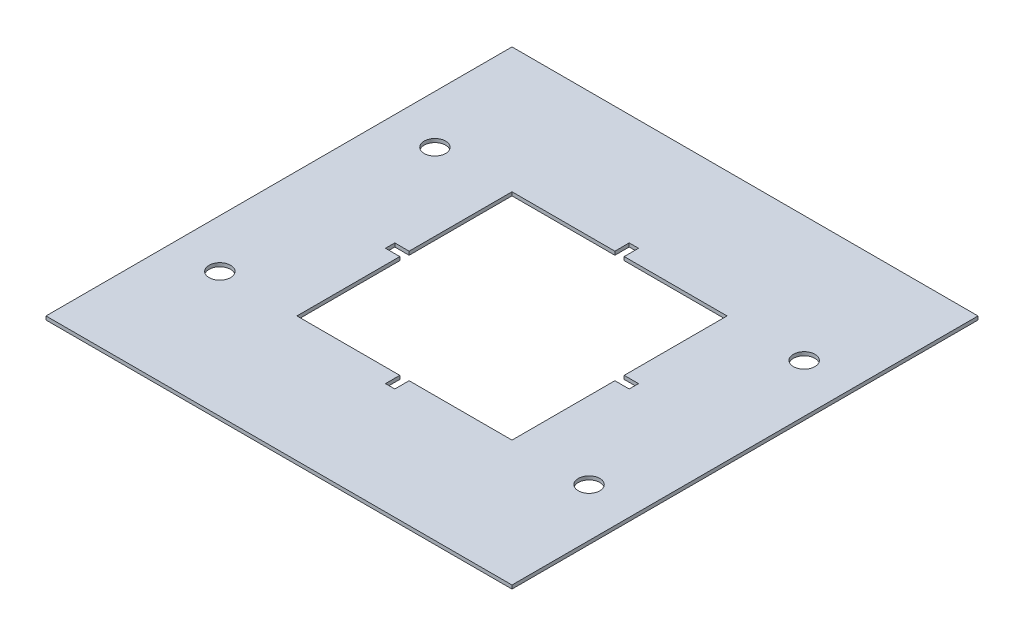
SolidWorks part; units mm, degrees
ref_plane "Alzado" through (0, 0, 0) normal (0, 0, 1) x (1, 0, 0)
ref_plane "Planta" through (0, 0, 0) normal (0, 1, 0) x (1, 0, 0)
ref_plane "Vista lateral" through (0, 0, 0) normal (1, 0, 0) x (0, 0, -1)
sketch "Croquis1" plane through (0, 0, 0) normal (0, 1, 0) x (1, 0, 0)
  line L0 (0, 0) -> (55, 55) construction
  line L1 (0, 0) -> (55, 0)
  line L2 (0, 0) -> (0, 55)
  line L3 (0, 55) -> (55, 55)
  line L4 (55, 0) -> (55, 55)
  line L5 (1.75, 0) -> (1.75, 55) construction
  line L6 (12.5, 12.5) -> (26.85, 12.5)
  line L7 (12.5, 12.5) -> (12.5, 26.85)
  line L8 (12.5, 42.5) -> (26.85, 42.5)
  line L9 (42.5, 12.5) -> (42.5, 26.85)
  line L10 (12.5, 12.5) -> (42.5, 42.5) construction
  line L11 (12.5, 42.5) -> (42.5, 12.5) construction
  line L12 (27.5, 0) -> (27.5, 55) construction
  line L13 (3.5, 0) -> (3.5, 55) construction
  line L14 (3.5, 27.5) -> (0, 27.5) construction
  line L15 (3.25, 42.5) -> (3.25, 27.5) construction
  line L16 (3.25, 27.5) -> (3.25, 12.5) construction
  line L17 (0, 27.5) -> (55, 27.5) construction
  line L18 (26.85, 44.5) -> (28.15, 44.5)
  line L19 (26.85, 44.5) -> (26.85, 42.5)
  line L21 (28.15, 44.5) -> (28.15, 42.5)
  line L22 (26.85, 44.5) -> (28.15, 42.5) construction
  line L23 (26.85, 42.5) -> (28.15, 44.5) construction
  line L25 (44.5, 28.15) -> (42.5, 28.15)
  line L26 (44.5, 28.15) -> (44.5, 26.85)
  line L27 (44.5, 26.85) -> (42.5, 26.85)
  line L29 (44.5, 28.15) -> (42.5, 26.85) construction
  line L30 (44.5, 26.85) -> (42.5, 28.15) construction
  line L31 (28.15, 10.5) -> (28.15, 12.5)
  line L32 (26.85, 10.5) -> (26.85, 12.5)
  line L33 (26.85, 10.5) -> (28.15, 10.5)
  line L34 (10.5, 26.85) -> (12.5, 26.85)
  line L36 (10.5, 28.15) -> (12.5, 28.15)
  line L37 (10.5, 28.15) -> (10.5, 26.85)
  line L38 (42.5, 28.15) -> (42.5, 42.5)
  line L39 (28.15, 12.5) -> (42.5, 12.5)
  line L40 (12.5, 28.15) -> (12.5, 42.5)
  line L41 (28.15, 42.5) -> (42.5, 42.5)
  circle A0 centre (1.75, 42.5) radius 1.5
  circle A1 centre (1.75, 12.5) radius 1.5
  circle A2 centre (53.25, 42.5) radius 1.5
  circle A3 centre (53.25, 12.5) radius 1.5
  point P4 (27.5, 27.5)
  point P18 (1.75, 27.5)
  point P25 (27.5, 43.5)
  point P35 (43.5, 27.5)
  dimension "D4" = 3
  dimension "D1" = 55
  dimension "D2" = 30
  dimension "D3" = 24
  dimension "D5" = 15
  dimension "D6" = 1.3
  dimension "D7" = 2
extrude "Saliente-Extruir1" add sketch "Croquis1" along normal blind 0.5
sketch "Croquis2" plane through (0, 0.5, 0) normal (0, 1, 0) x (1, 0, 0)
  line L0 (27.5, 60) -> (27.5, 55) construction
  line L1 (-5, -5) -> (60, -5)
  line L2 (-5, -5) -> (-5, 60)
  line L3 (-5, 60) -> (60, 60)
  line L4 (0, 55) -> (0, 0)
  line L5 (0, 0) -> (55, 0)
  line L6 (55, 0) -> (55, 55)
  line L7 (55, 55) -> (0, 55)
  line L8 (0, 55) -> (0, 0)
  line L9 (0, 0) -> (55, 0)
  line L10 (55, 0) -> (55, 55)
  line L11 (55, 55) -> (0, 55)
  line L12 (60, -5) -> (60, 60)
  line L13 (55, 27.5) -> (60, 27.5) construction
  point P12 (66.1407, 65.9407)
  dimension "D2" = 65
  dimension "D1" = 0
extrude "Saliente-Extruir2" add sketch "Croquis2" against normal up to surface (0.5 mm away) up to face at (53.25, 0, -44)
